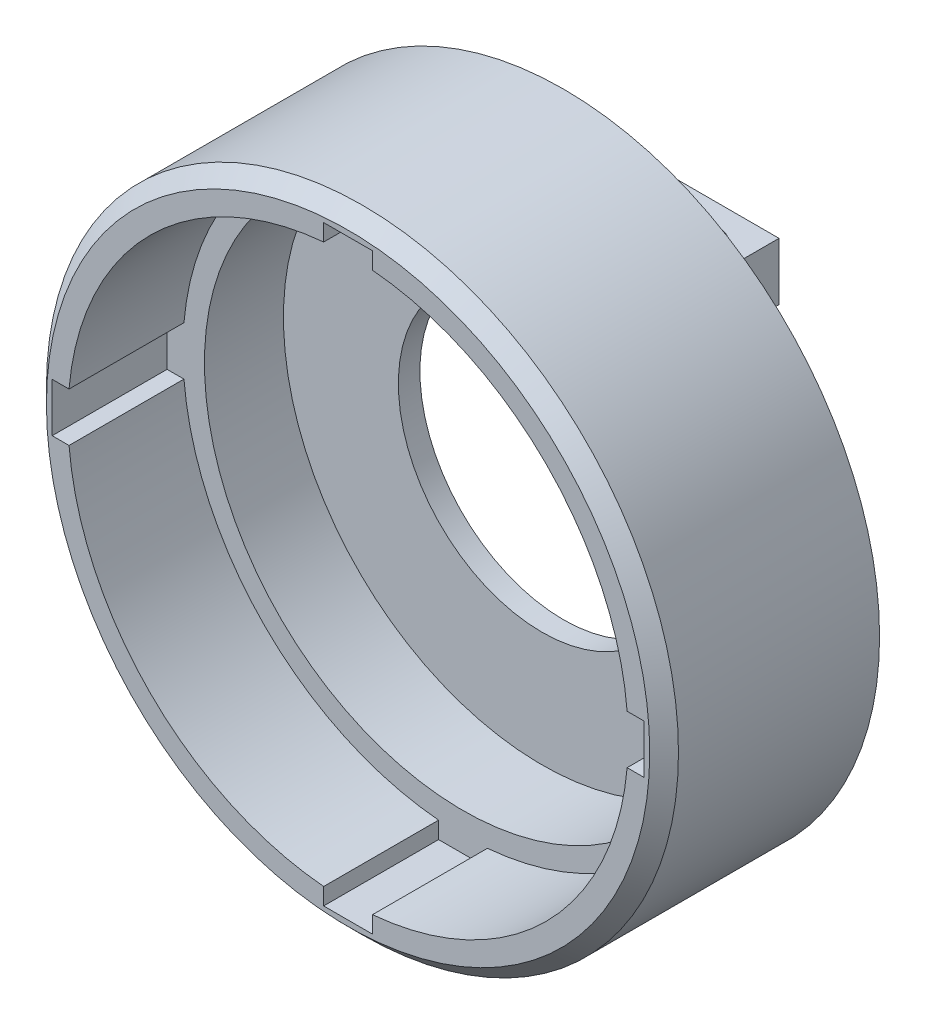
SolidWorks part; units mm, degrees
ref_plane "Front Plane" through (0, 0, 0) normal (0, 0, 1) x (1, 0, 0)
ref_plane "Top Plane" through (0, 0, 0) normal (0, 1, 0) x (1, 0, 0)
ref_plane "Right Plane" through (0, 0, 0) normal (1, 0, 0) x (0, 0, -1)
sketch "Sketch1" plane through (0, 0, 0) normal (0, 0, 1) x (1, 0, 0)
  circle A0 centre (0, 0) radius 22
  dimension "D1" = 44
extrude "Boss-Extrude1" add sketch "Sketch1" along normal mid plane 16.5
sketch "Sketch2" plane through (0, 0, 8.25) normal (0, 0, 1) x (1, 0, 0)
  circle A0 centre (0, 0) radius 18
  dimension "D1" = 36
extrude "Cut-Extrude1" cut sketch "Sketch2" against normal blind 13.5
sketch "Sketch3" plane through (0, 0, 8.25) normal (0, 0, 1) x (1, 0, 0)
  circle A0 centre (0, 0) radius 19.5
  dimension "D1" = 39
extrude "Cut-Extrude2" cut sketch "Sketch3" against normal blind 8
sketch "Sketch4" plane through (0, 0, -8.25) normal (0, 0, -1) x (-1, 0, 0)
  circle A0 centre (0, 0) radius 10
  dimension "D1" = 20
extrude "Cut-Extrude3" cut sketch "Sketch4" against normal through all both and the other way through all
sketch "Sketch6" plane through (0, 0, 8.25) normal (0, 0, 1) x (1, 0, 0)
  line L1 (1.7, 20.6) -> (-1.7, 20.6)
  line L2 (1.7, 20.6) -> (1.7, 18.4)
  line L3 (1.7, 18.4) -> (-1.7, 18.4)
  line L4 (-1.7, 20.6) -> (-1.7, 18.4)
  line L5 (1.7, 20.6) -> (-1.7, 18.4) construction
  line L6 (1.7, 18.4) -> (-1.7, 20.6) construction
  circle A0 centre (0, 0) radius 19.5 construction
  circle A1 centre (0, 0) radius 19.5 construction
  point P0 (0, 19.5)
  dimension "D1" = 2.2
  dimension "D2" = 3.4
extrude "Cut-Extrude5" cut sketch "Sketch6" against normal up to surface (8 mm away) up to face at (19.5, 0, 0.25)
pattern_circular "CirPattern1" count 4 over 360 about axis through (0, 0, 0) along (0, 0, 1) of "Cut-Extrude5"
sketch "Sketch7" plane through (0, 0, -8.25) normal (0, 0, -1) x (-1, 0, 0)
  circle A0 centre (0, 0) radius 22
extrude "Cut-Extrude6" cut sketch "Sketch7" against normal blind 1.5
chamfer "Chamfer1" distance 1 angle 45 1 edges at (22, 0, 8.25)
sketch "Sketch8" plane through (0, 0, -6.75) normal (0, 0, -1) x (-1, 0, 0)
  line L0 (0, 22) -> (0, -22) construction
  line L1 (-20.2916, 8.5) -> (20.2916, 8.5) construction
  line L2 (-5, 11.5) -> (-10, 11.5)
  line L3 (5, 9) -> (-5, 9)
  line L4 (5, 9) -> (5, 14)
  line L5 (5, 14) -> (-5, 14)
  line L6 (-5, 9) -> (-5, 14)
  line L7 (5, 9) -> (-5, 14) construction
  line L8 (5, 14) -> (-5, 9) construction
  line L9 (-10, 11.5) -> (-10, 15.5)
  line L10 (-10, 15.5) -> (10, 15.5)
  line L11 (10, 15.5) -> (10, 11.5)
  line L12 (10, 11.5) -> (5, 11.5)
  circle A0 centre (0, 0) radius 22 construction
  point P7 (0, 11.5)
  point P17 (0, 15.5)
  circle M10 centre (0, 0) radius 10
  dimension "D1" = 8.5
  dimension "D2" = 10
  dimension "D3" = 5
  dimension "D4" = 20
  dimension "D5" = 4
  dimension "D6" = 3
extrude "Boss-Extrude2" add sketch "Sketch8" along normal blind 5 contours L6 L3 L4 L5 M10 | L12 L11 L10 L9 L2 L6 L5 L4
sketch "Sketch9" plane through (0, 0, -11.75) normal (0, 0, -1) x (-1, 0, 0)
  line L0 (-5, 13.5) -> (-5, 8.5)
  line L1 (-5, 8.5) -> (5, 8.5)
  line L2 (5, 8.5) -> (5, 13.5)
  line L3 (5, 13.5) -> (-5, 13.5)
  line L4 (0, 0) -> (0, 22) construction
  line L5 (-20.2916, 8.5) -> (20.2916, 8.5) construction
  line L9 (-10, 11.5) -> (10, 11.5) construction
  line L10 (-5, 11.5) -> (5, 11.5) construction
  circle A0 centre (0, 0) radius 22 construction
  point P15 (0, 13.5)
  dimension "D1" = 5
  dimension "D2" = 8.5
  dimension "D3" = 10
  dimension "D4" = 2
extrude "Cut-Extrude7" cut sketch "Sketch9" against normal through all
sketch "Sketch10" plane through (0, 11.5, 0) normal (0, -1, 0) x (1, 0, 0)
  line L0 (-7.5, -11.75) -> (-7.5, -6.75) construction
  line L1 (-10, -11.75) -> (-5, -11.75) construction
  line L2 (-10, -6.75) -> (-5, -6.75) construction
  line L3 (-10, -9.25) -> (-5, -9.25) construction
  line L4 (-10, -11.75) -> (-10, -6.75) construction
  line L5 (-5, -11.75) -> (-5, -6.75) construction
  line L6 (0, -11.75) -> (0, -6.75) construction
  line L7 (-5, -11.75) -> (5, -11.75) construction
  line L8 (-22, -6.75) -> (22, -6.75) construction
  circle A0 centre (-7.5, -9.25) radius 1
  circle A1 centre (7.5, -9.25) radius 1
  dimension "D1" = 2
extrude "Cut-Extrude8" cut sketch "Sketch10" against normal through all
